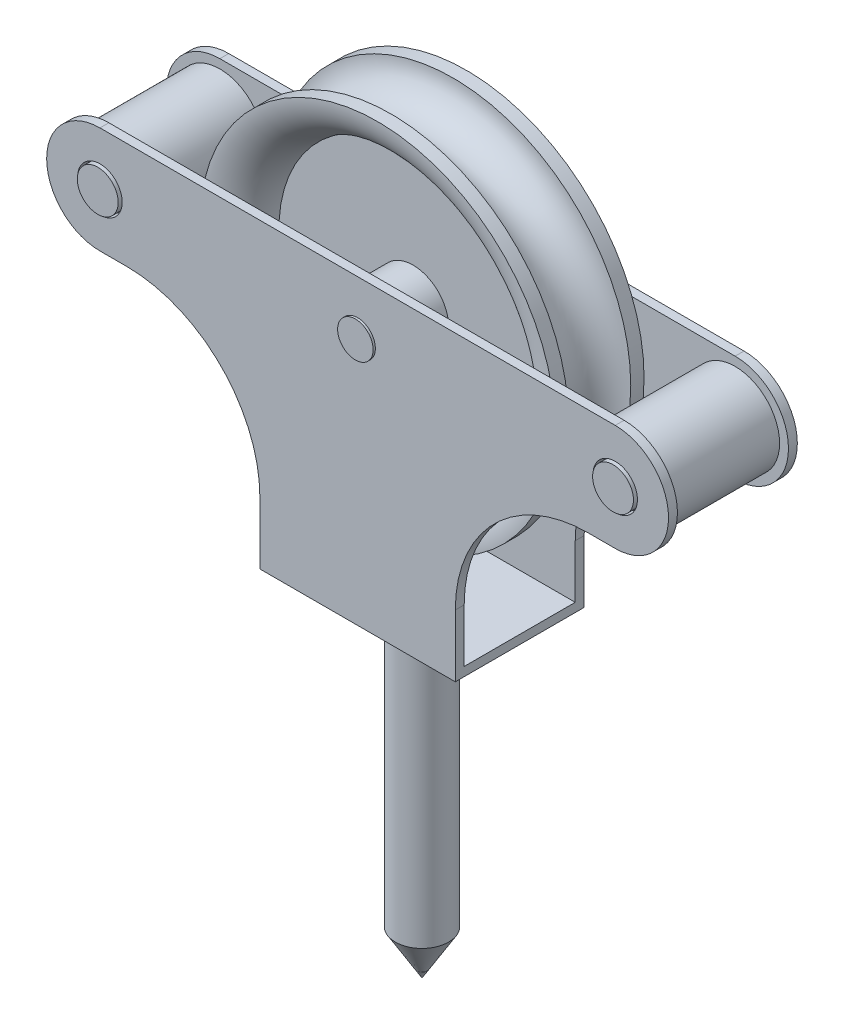
SolidWorks part; units mm, degrees
ref_plane "Front Plane" through (0, 0, 0) normal (0, 0, 1) x (1, 0, 0)
ref_plane "Top Plane" through (0, 0, 0) normal (0, 1, 0) x (1, 0, 0)
ref_plane "Right Plane" through (0, 0, 0) normal (1, 0, 0) x (0, 0, -1)
sketch "Sketch1" plane through (0, 0, 0) normal (1, 0, 0) x (0, 0, -1)
  line L0 (-12.4863, 0) -> (11.3362, 0) construction
  line L1 (55, 0) -> (-55, 0) construction
  line L2 (-7.5, 0) -> (-7.5, 2)
  line L3 (-7.5, 2) -> (-5, 2)
  line L4 (-5, 2) -> (-5, 4)
  line L5 (-5, 4) -> (-1, 4)
  line L6 (-1, 4) -> (-1, 15.101)
  line L7 (0, 55) -> (0, -55) construction
  line L8 (-5, 20) -> (-3.5, 20)
  line L9 (3.5, 20) -> (5, 20)
  line L10 (0, 10.4772) -> (0, 8.593) construction
  line L11 (7.5, 0) -> (7.5, 2)
  line L12 (7.5, 2) -> (5, 2)
  line L13 (5, 2) -> (5, 4)
  line L14 (5, 4) -> (1, 4)
  line L15 (1, 4) -> (1, 15.101)
  line L16 (-7.5, 0) -> (7.5, 0)
  arc A0 (-3.5, 20) -> (3.5, 20) centre (0, 20) ccw
  arc A1 (-5, 20) -> (-1, 15.101) centre (0, 20) ccw
  arc A2 (1, 15.101) -> (5, 20) centre (0, 20) ccw
  dimension "D1" = 10
  dimension "D2" = 7
  dimension "D3" = 20
  dimension "D4" = 7.5
  dimension "D5" = 1
  dimension "D6" = 2
  dimension "D7" = 4
revolve "Revolve1" add sketch "Sketch1" angle 360 about L0
sketch "Sketch3" plane through (0, 0, 0) normal (0, 0, 1) x (1, 0, 0)
  line L0 (-29.0033, 6) -> (29.0033, 6)
  line L1 (0, -8.25) -> (0, 8.25) construction
  line L2 (-29.0033, -6) -> (-26, -6)
  line L3 (-11, -21) -> (-11, -28)
  line L4 (-11, -28) -> (11, -28)
  line L5 (0, -18.4157) -> (0, -30.129) construction
  line L6 (8.25, 0) -> (-8.25, 0) construction
  line L7 (11, -21) -> (11, -28)
  line L8 (29.0033, -6) -> (26, -6)
  circle A0 centre (-29.0033, 0) radius 2.5
  arc A1 (-29.0033, 6) -> (-29.0033, -6) centre (-29.0033, 0) ccw
  arc A2 (-11, -21) -> (-26, -6) centre (-26, -21) ccw
  arc A3 (11, -21) -> (26, -6) centre (26, -21) cw
  arc A4 (29.0033, 6) -> (29.0033, -6) centre (29.0033, 0) cw
  circle A5 centre (29.0033, 0) radius 2.5
  point P11 (0, 6)
  point P25 (0, -28)
  dimension "D1" = 12
  dimension "D2" = 5
  dimension "D3" = 15
  dimension "D4" = 11
  dimension "D5" = 28
extrude "Boss-Extrude1" add sketch "Sketch3" along normal mid plane 14.5 separate body
sketch "Sketch4" plane through (0, 0, 0) normal (1, 0, 0) x (0, 0, -1)
  line L31 (-6.25, 6) -> (6.25, 6)
  line L38 (6.25, -27) -> (6.25, -21)
  line L39 (6.25, -21) -> (6.25, -6)
  line L40 (6.25, -6) -> (6.25, 6)
  line L41 (-6.25, 6) -> (-6.25, -6)
  line L42 (-6.25, -6) -> (-6.25, -21)
  line L43 (-6.25, -21) -> (-6.25, -27)
  line L44 (-6.25, -27) -> (6.25, -27)
  line L45 (6.25, -27) -> (6.25, -21)
  line L46 (6.25, -21) -> (6.25, -6)
  line L47 (6.25, -6) -> (6.25, 6)
  line L48 (-6.25, 6) -> (-6.25, -6)
  line L49 (-6.25, -6) -> (-6.25, -21)
  line L50 (-6.25, -21) -> (-6.25, -27)
  line L51 (-6.25, -27) -> (6.25, -27)
  dimension "D1" = 1
extrude "Cut-Extrude3" cut sketch "Sketch4" against normal mid plane 80
sketch "Sketch5" plane through (0, -28, 0) normal (0, -1, 0) x (1, 0, 0)
  circle A0 centre (0, 0) radius 3
extrude "Boss-Extrude2" add sketch "Sketch5" along normal blind 38
chamfer "Chamfer1" distance 5 distance2 3 1 edges at (0, -66, -3)
sketch "Sketch6" plane through (0, 0, 0) normal (0, 1, 0) x (1, 0, 0)
  line L0 (-29.0033, 10.0154) -> (-29.0033, -9.4371) construction
  line L1 (-29.0033, 7.5) -> (-29.0033, -7.5)
  line L4 (-29.0033, 7.5) -> (-31.3033, 7.5)
  line L5 (-31.3033, 7.5) -> (-31.3033, 6.25)
  line L6 (-31.5033, 6.25) -> (-26.5033, 6.25) construction
  line L7 (-31.3033, 6.25) -> (-34.0033, 6.25)
  line L8 (-35.0033, 6.25) -> (-29.0033, 6.25) construction
  line L9 (-34.0033, 6.25) -> (-34.0033, -6.25)
  line L10 (-29.0033, -6.25) -> (-35.0033, -6.25) construction
  line L11 (-34.0033, -6.25) -> (-31.3033, -6.25)
  line L12 (-26.5033, -6.25) -> (-31.5033, -6.25) construction
  line L13 (-31.3033, -6.25) -> (-31.3033, -7.5)
  line L14 (-31.3033, -7.5) -> (-29.0033, -7.5)
  line L15 (-38.5037, 0) -> (38.5037, 0) construction
  dimension "D1" = 15
  dimension "D2" = 7.5
  dimension "D3" = 5
  dimension "D4" = 2.3
  dimension "D5" = 2.3
revolve "Revolve6" add sketch "Sketch6" angle 360 about L0
pattern_circular "CirPattern3" count 2 over 360 about axis through (0, 0, 0) along (0, 0, 1) of bodies 106
sketch "Sketch7" plane through (0, 0, 0) normal (0, 0, 1) x (1, 0, 0)
  line L0 (0, 16.4853) -> (92.3023, 16.4853)
  line L1 (0, -8.25) -> (0, 8.25) construction
  line L2 (16.8338, 0) -> (16.8338, -66.6023)
  line L3 (8.25, 0) -> (-8.25, 0) construction
